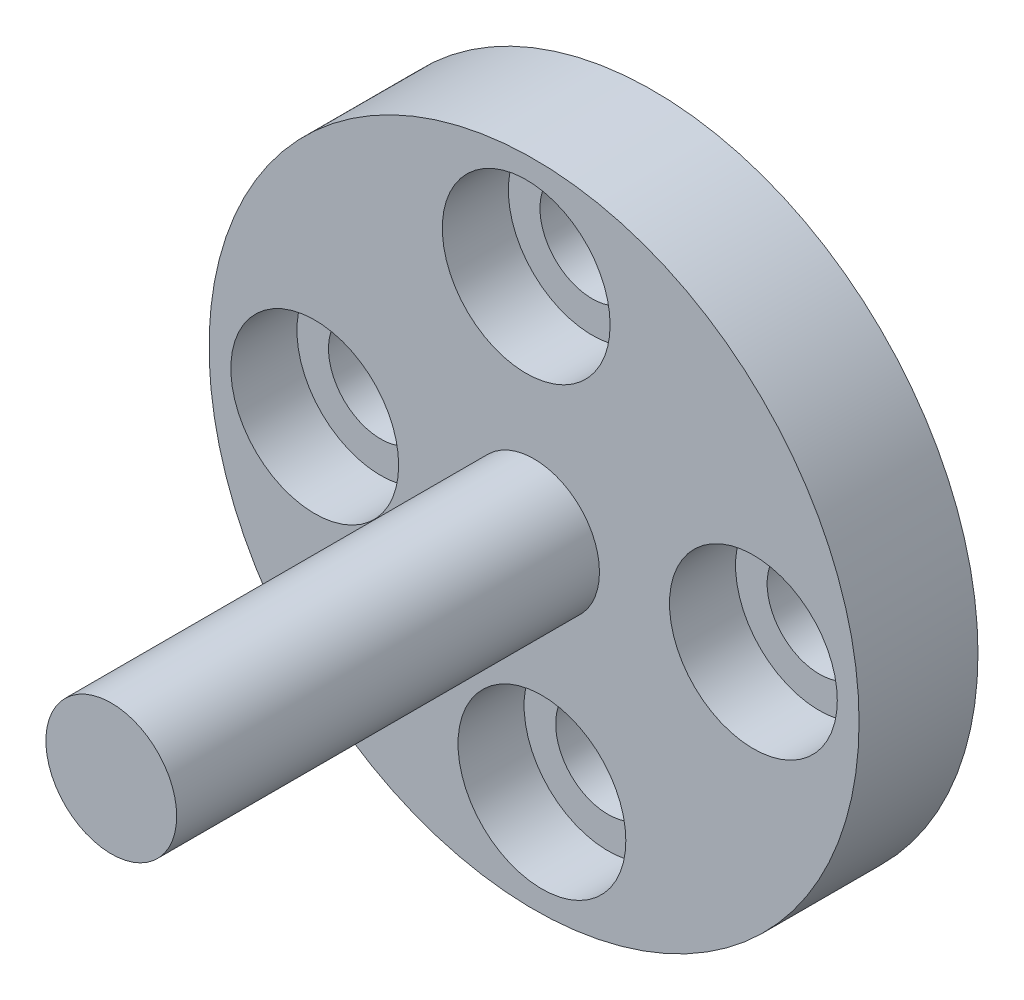
SolidWorks part; units mm, degrees
ref_plane "Plan de face" through (0, 0, 0) normal (0, 0, 1) x (1, 0, 0)
ref_plane "Plan de dessus" through (0, 0, 0) normal (0, 1, 0) x (1, 0, 0)
ref_plane "Plan de droite" through (0, 0, 0) normal (1, 0, 0) x (0, 0, -1)
sketch "Esquisse1" plane through (0, 0, 0) normal (0, 0, 1) x (1, 0, 0)
  circle A0 centre (0, 0) radius 12.3
  circle A1 centre (-8.3, -0.2975) radius 1.9799
  circle A2 centre (-0.2975, 8.3) radius 1.9799
  circle A3 centre (8.3, 0.2975) radius 1.9799
  circle A4 centre (0.2975, -8.3) radius 1.9799
  circle A5 centre (0, 0) radius 3
  point P14 (0, 0)
  dimension "D1" = 8.3
  dimension "D4" = 24.6
  dimension "D3" = 16.6
  dimension "D2" = 4
extrude "Boss.-Extru.1" add sketch "Esquisse1" along normal blind 2
sketch "Esquisse2" plane through (0, 0, 2) normal (0, 0, 1) x (1, 0, 0)
  line L0 (2.878, 8.3) -> (1.2903, 11.05) construction
  line L1 (-8.3, 2.878) -> (-11.05, 1.2903)
  line L2 (-11.05, 1.2903) -> (-11.05, -1.8852)
  line L3 (-11.05, -1.8852) -> (-8.3, -3.4729)
  line L4 (-8.3, -3.4729) -> (-5.55, -1.8852)
  line L5 (-5.55, -1.8852) -> (-5.55, 1.2903)
  line L6 (-5.55, 1.2903) -> (-8.3, 2.878)
  line L7 (1.2903, 11.05) -> (-1.8852, 11.05) construction
  line L8 (-1.8852, 11.05) -> (-3.4729, 8.3) construction
  line L9 (-3.4729, 8.3) -> (-1.8852, 5.55) construction
  line L10 (-1.8852, 5.55) -> (1.2903, 5.55) construction
  line L11 (1.2903, 5.55) -> (2.878, 8.3) construction
  line L12 (8.3, -2.878) -> (11.05, -1.2903) construction
  line L13 (11.05, -1.2903) -> (11.05, 1.8852) construction
  line L14 (11.05, 1.8852) -> (8.3, 3.4729) construction
  line L15 (8.3, 3.4729) -> (5.55, 1.8852) construction
  line L16 (5.55, 1.8852) -> (5.55, -1.2903) construction
  line L17 (5.55, -1.2903) -> (8.3, -2.878) construction
  line L18 (-2.878, -8.3) -> (-1.2903, -11.05) construction
  line L19 (-1.2903, -11.05) -> (1.8852, -11.05) construction
  line L20 (1.8852, -11.05) -> (3.4729, -8.3) construction
  line L21 (3.4729, -8.3) -> (1.8852, -5.55) construction
  line L22 (1.8852, -5.55) -> (-1.2903, -5.55) construction
  line L23 (-1.2903, -5.55) -> (-2.878, -8.3) construction
  circle A0 centre (-8.3, -0.2975) radius 2.75 construction
  circle A1 centre (0, 0) radius 12.3
  circle A2 centre (0, 0) radius 12.3
  circle A3 centre (-8.3, -0.2975) radius 3.1754
  circle A4 centre (-0.2975, 8.3) radius 3.1754
  circle A5 centre (8.3, 0.2975) radius 3.1754
  circle A6 centre (0.2975, -8.3) radius 3.1754
  point P33 (0, 0)
  point P41 (0, 0)
  circle M9 centre (0, 0) radius 3
  circle M10 centre (0, 0) radius 12.3
  dimension "D5" = 4
  dimension "D2" = 5.5
  dimension "D3" = 6.3509
  dimension "D1" = 0
  dimension "D4" = 4
extrude "Boss.-Extru.2" add sketch "Esquisse2" along normal blind 2.5 contours A6 A5 A4 A3 M10 M9 | M9
sketch "Esquisse3" plane through (0, 0, 4.5) normal (0, 0, 1) x (1, 0, 0)
  circle A0 centre (0, 0) radius 2.475
  dimension "D1" = 4.95
extrude "Boss.-Extru.3" add sketch "Esquisse3" along normal blind 16
